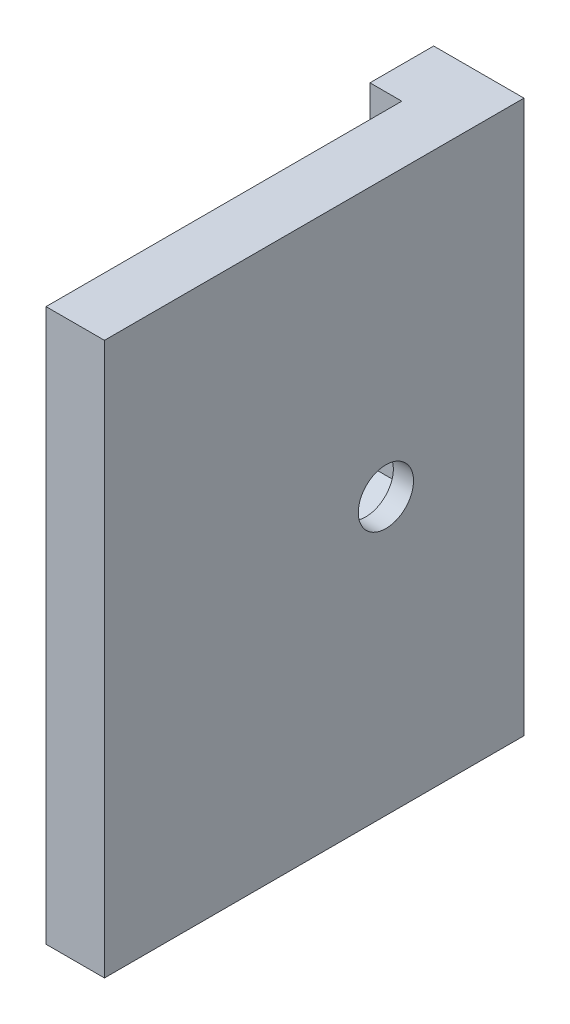
SolidWorks part; units mm, degrees
ref_plane "Front Plane" through (0, 0, 0) normal (0, 0, 1) x (1, 0, 0)
ref_plane "Top Plane" through (0, 0, 0) normal (0, 1, 0) x (1, 0, 0)
ref_plane "Right Plane" through (0, 0, 0) normal (1, 0, 0) x (0, 0, -1)
ref_plane "Plane1" through (330.5, 0, 0) normal (1, 0, 0) x (0, 0, -1)
sketch "Sketch1" plane through (330.5, 0, 0) normal (1, 0, 0) x (0, 0, -1)
  line L0 (-287, 274) -> (-326.5, 274)
  line L1 (-326.5, 274) -> (-326.5, 326)
  line L2 (-326.5, 326) -> (-287, 326)
  line L3 (-287, 326) -> (-287, 274)
  circle A0 centre (-300, 300) radius 2.6
extrude "Boss-Extrude1" add sketch "Sketch1" along normal blind 5.5
sketch "Sketch2" plane through (330.5, 0, 0) normal (1, 0, 0) x (0, 0, -1)
  line L0 (-304.1, 302.3671) -> (-300, 304.7343)
  line L1 (-300, 304.7343) -> (-295.9, 302.3671)
  line L2 (-295.9, 302.3671) -> (-295.9, 297.6329)
  line L3 (-295.9, 297.6329) -> (-300, 295.2657)
  line L4 (-300, 295.2657) -> (-304.1, 297.6329)
  line L5 (-304.1, 297.6329) -> (-304.1, 302.3671)
extrude "Cut-Extrude1" cut sketch "Sketch2" along normal blind 3.6
ref_plane "Plane2" through (0, 0, 287) normal (0, 0, 1) x (1, 0, 0)
sketch "Sketch3" plane through (0, 0, 287) normal (0, 0, 1) x (1, 0, 0)
  line L0 (327.5, 274) -> (336, 274)
  line L1 (336, 274) -> (336, 326)
  line L2 (336, 326) -> (327.5, 326)
  line L3 (327.5, 326) -> (327.5, 274)
extrude "Boss-Extrude2" add sketch "Sketch3" along normal blind 6
sketch "Sketch4" plane through (0, 0, 287) normal (0, 0, 1) x (1, 0, 0)
  circle A0 centre (329.3, 283) radius 5.05
  circle A1 centre (329.3, 283) radius 1.7
extrude "Boss-Extrude3" add sketch "Sketch4" along normal blind 6
sketch "Sketch5" plane through (0, 0, 287) normal (0, 0, 1) x (1, 0, 0)
  circle A0 centre (329.3, 317) radius 5.05
  circle A1 centre (329.3, 317) radius 1.7
extrude "Boss-Extrude4" add sketch "Sketch5" along normal blind 6
sketch "Sketch6" plane through (0, 0, 287) normal (0, 0, 1) x (1, 0, 0)
  circle A0 centre (329.3, 283) radius 1.7
  circle A1 centre (329.3, 317) radius 1.7
extrude "Cut-Extrude2" cut sketch "Sketch6" along normal blind 6
